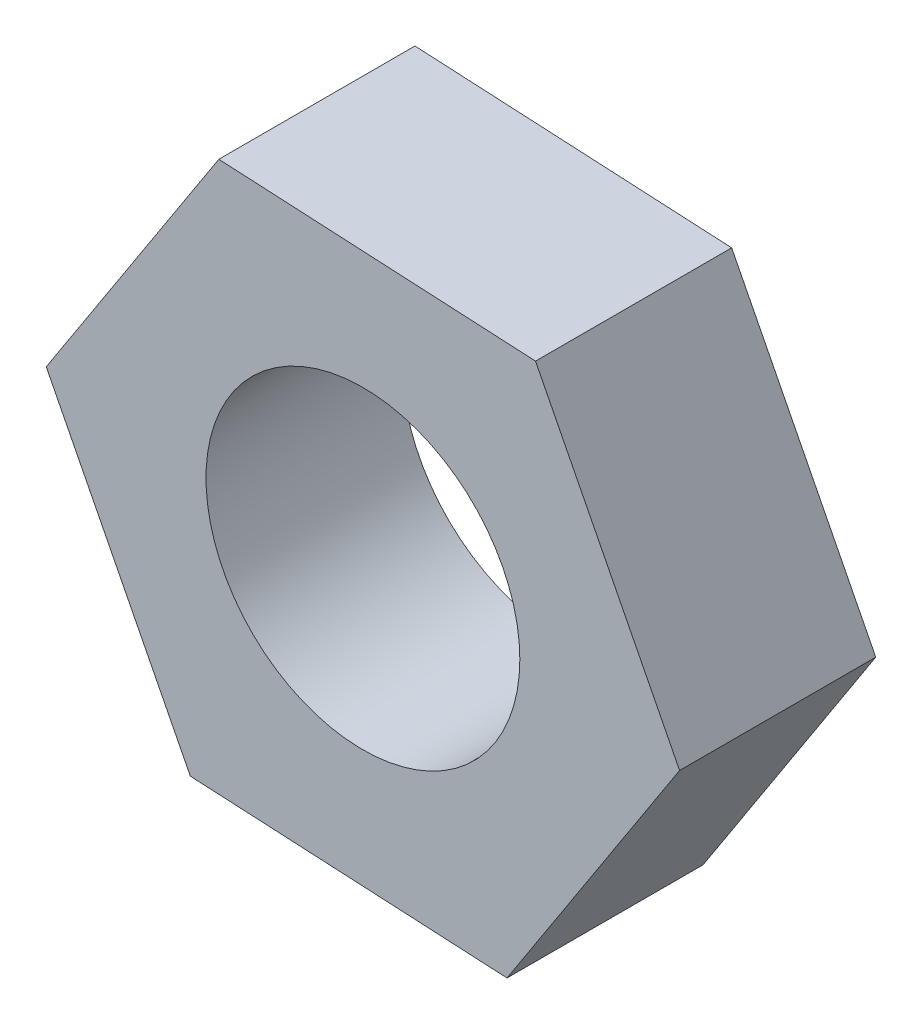
SolidWorks part; units mm, degrees
ref_plane "Спереди" through (0, 0, 0) normal (0, 0, 1) x (1, 0, 0)
ref_plane "Сверху" through (0, 0, 0) normal (0, 1, 0) x (1, 0, 0)
ref_plane "Справа" through (0, 0, 0) normal (1, 0, 0) x (0, 0, -1)
sketch "Эскиз1" plane through (0, 0, 0) normal (0, 0, 1) x (1, 0, 0)
  line L1 (2.1996, 3.3904) -> (-1.8364, 3.6002)
  line L2 (-1.8364, 3.6002) -> (-4.036, 0.2097)
  line L3 (-4.036, 0.2097) -> (-2.1996, -3.3904)
  line L4 (-2.1996, -3.3904) -> (1.8364, -3.6002)
  line L5 (1.8364, -3.6002) -> (4.036, -0.2097)
  line L6 (4.036, -0.2097) -> (2.1996, 3.3904)
  circle A0 centre (0, 0) radius 3.5 construction
  dimension "D1" = 7
extrude "Основание-Вытянуть" add sketch "Эскиз1" along normal blind 2.5
sketch "Эскиз2" plane through (0, 0, 2.5) normal (0, 0, 1) x (1, 0, 0)
  circle A0 centre (0, 0) radius 2
  dimension "D1" = 4
extrude "Вырез-Вытянуть1" cut sketch "Эскиз2" against normal through all
